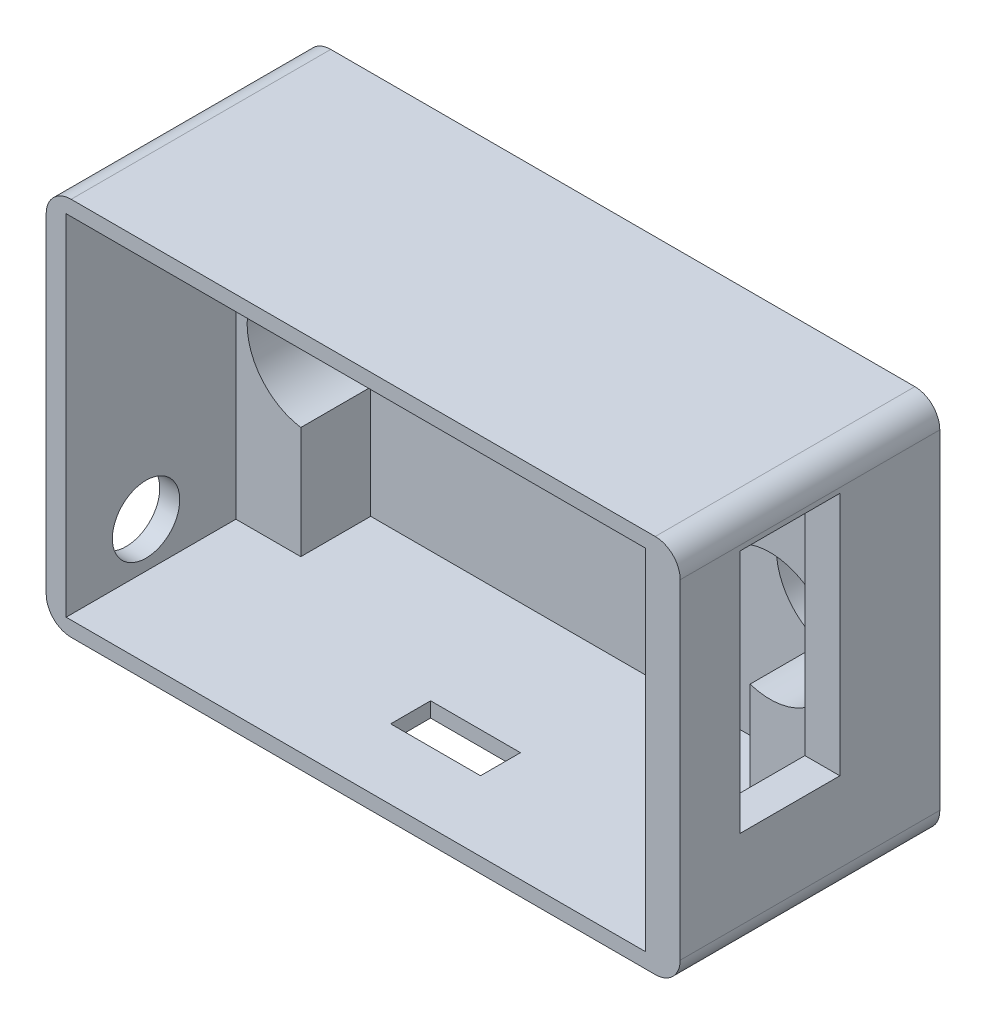
SolidWorks part; units mm, degrees
ref_plane "Front Plane" through (0, 0, 0) normal (0, 0, 1) x (1, 0, 0)
ref_plane "Top Plane" through (0, 0, 0) normal (0, 1, 0) x (1, 0, 0)
ref_plane "Right Plane" through (0, 0, 0) normal (1, 0, 0) x (0, 0, -1)
sketch "Sketch1" plane through (0, 0, 0) normal (0, 0, 1) x (1, 0, 0)
  line L1 (0, 0) -> (63.5, 0)
  line L2 (0, 0) -> (0, 38)
  line L3 (0, 38) -> (63.5, 38)
  line L4 (63.5, 0) -> (63.5, 38)
  dimension "D1" = 63.5
  dimension "D2" = 38
extrude "Boss-Extrude1" add sketch "Sketch1" along normal blind 26
sketch "Sketch2" plane through (0, 0, 26) normal (0, 0, 1) x (1, 0, 0)
  line L0 (63.5, 38) -> (0, 38) construction
  line L1 (2, 36.5) -> (60, 36.5)
  line L2 (2, 36.5) -> (2, 1.5)
  line L3 (2, 1.5) -> (60, 1.5)
  line L4 (60, 36.5) -> (60, 1.5)
  line L6 (0, 38) -> (0, 0) construction
  dimension "D1" = 35
  dimension "D2" = 1.5
  dimension "D3" = 2
  dimension "D4" = 58
extrude "Cut-Extrude1" cut sketch "Sketch2" against normal blind 17
sketch "Sketch4" plane through (0, 0, 9) normal (0, 0, 1) x (1, 0, 0)
  line L1 (8.5, 36.5) -> (53.5, 36.5)
  line L2 (8.5, 36.5) -> (8.5, 1.5)
  line L3 (8.5, 1.5) -> (53.5, 1.5)
  line L4 (53.5, 36.5) -> (53.5, 1.5)
  line L5 (2, 1.5) -> (60, 1.5) construction
  line L6 (2, 36.5) -> (2, 1.5) construction
  dimension "D1" = 35
  dimension "D2" = 45
  dimension "D3" = 0
  dimension "D4" = 6.5
extrude "Cut-Extrude3" cut sketch "Sketch4" against normal blind 7
sketch "Sketch5" plane through (0, 0, 0) normal (0, 0, -1) x (-1, 0, 0)
  line L0 (-63.5, 0) -> (-63.5, 38) construction
  line L2 (-63.5, 38) -> (0, 38) construction
  circle A0 centre (-55.5, 19) radius 6.375
  circle A1 centre (-9.5, 19) radius 6.375
  dimension "D1" = 12.75
  dimension "D2" = 12.75
  dimension "D4" = 8
  dimension "D5" = 19
  dimension "D3" = 46
extrude "Cut-Extrude4" cut sketch "Sketch5" against normal blind 9
sketch "Sketch6" plane through (63.5, 0, 0) normal (1, 0, 0) x (0, 0, -1)
  line L0 (-26, 0) -> (-26, 38) construction
  line L1 (-20, 35) -> (-10.0107, 35)
  line L2 (-20, 35) -> (-20, 10.5)
  line L3 (-20, 10.5) -> (-10.0107, 10.5)
  line L4 (-10.0107, 35) -> (-10.0107, 10.5)
  line L5 (-26, 38) -> (0, 38) construction
  dimension "D1" = 6
  dimension "D2" = 3
  dimension "D3" = 24.5
extrude "Cut-Extrude5" cut sketch "Sketch6" against normal blind 17
sketch "Sketch7" plane through (0, 0, 0) normal (-1, 0, 0) x (0, 0, 1)
  line L0 (26, 38) -> (26, 0) construction
  line L1 (26, 38) -> (0, 38) construction
  circle A0 centre (18, 6) radius 3.375
  dimension "D1" = 6.75
  dimension "D3" = 32
  dimension "D2" = 8
extrude "Cut-Extrude6" cut sketch "Sketch7" against normal blind 7
sketch "Sketch8" plane through (0, 0, 0) normal (0, -1, 0) x (1, 0, 0)
  line L0 (63.5, 26) -> (63.5, 0) construction
  line L1 (27.5, 19) -> (36.5, 19)
  line L2 (27.5, 19) -> (27.5, 15)
  line L3 (27.5, 15) -> (36.5, 15)
  line L4 (36.5, 19) -> (36.5, 15)
  line L7 (0, 0) -> (63.5, 0) construction
  dimension "D1" = 9
  dimension "D2" = 4
  dimension "D3" = 27
  dimension "D4" = 15
extrude "Cut-Extrude7" cut sketch "Sketch8" against normal blind 7
fillet "Fillet1" radius 2.5 4 edges at (63.5, 38, 13) (63.5, 0, 13) (0, 0, 13) (0, 38, 13)
